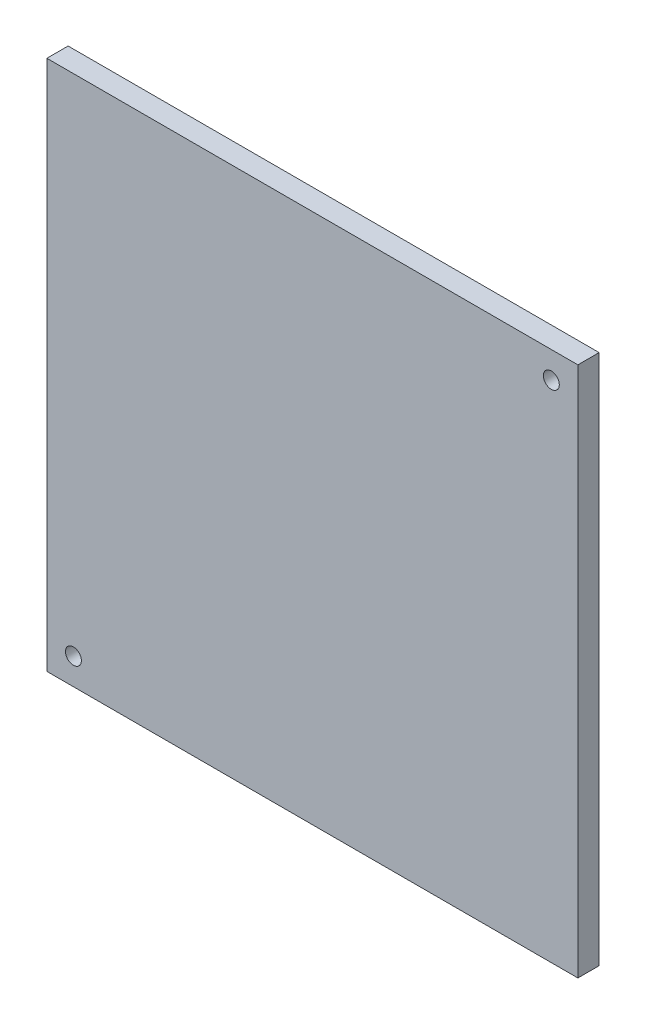
SolidWorks part; units mm, degrees
ref_plane "前视基准面" through (0, 0, 0) normal (0, 0, 1) x (1, 0, 0)
ref_plane "上视基准面" through (0, 0, 0) normal (0, 1, 0) x (1, 0, 0)
ref_plane "右视基准面" through (0, 0, 0) normal (1, 0, 0) x (0, 0, -1)
sketch "草图1" plane through (0, 0, 0) normal (0, 0, 1) x (1, 0, 0)
  line L1 (50, -50) -> (-50, -50)
  line L2 (50, -50) -> (50, 50)
  line L3 (50, 50) -> (-50, 50)
  line L4 (-50, -50) -> (-50, 50)
  line L5 (50, -50) -> (-50, 50) construction
  line L6 (50, 50) -> (-50, -50) construction
  circle A1 centre (0, 0) radius 60 construction
  circle A2 centre (0, 0) radius 90
  circle A3 centre (-51.9615, -30) radius 1.6
  circle A5 centre (0, 60) radius 1.6
  circle A7 centre (51.9615, -30) radius 1.6
  circle A8 centre (-45, -45) radius 1.5
  circle A9 centre (45, 45) radius 1.5
  point P3 (0, 0)
  point P7 (0, 0)
  point P10 (0, 60)
  dimension "D4" = 3
  dimension "D5" = 5
  dimension "D6" = 5
  dimension "D7" = 3
  dimension "D8" = 5
  dimension "D9" = 5
  dimension "D1" = 3.2
  dimension "D10" = 3.2
  dimension "D11" = 3.2
  dimension "D12" = 180
  dimension "D13" = 120
  dimension "D2" = 100
  dimension "D3" = 100
extrude "凸台-拉伸1" add sketch "草图1" along normal blind 4 contours L4 L1 L2 L3 A9 A8
